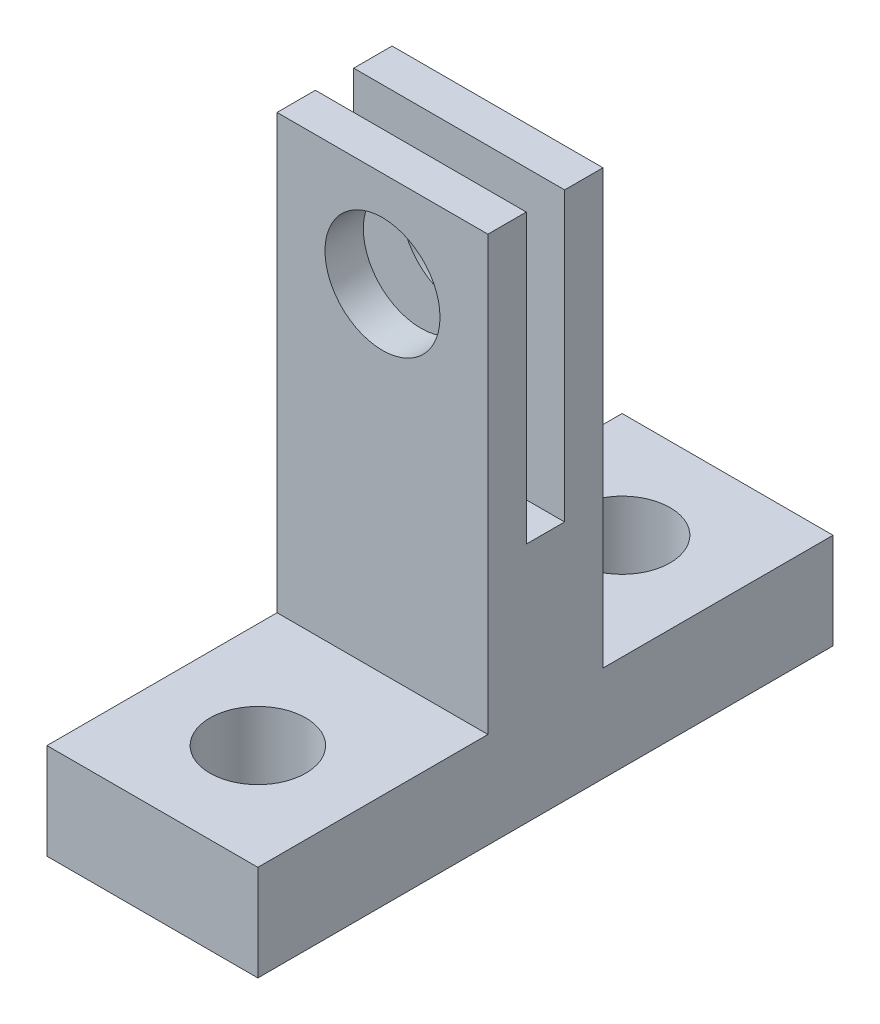
SolidWorks part; units mm, degrees
ref_plane "Front Plane" through (0, 0, 0) normal (0, 0, 1) x (1, 0, 0)
ref_plane "Top Plane" through (0, 0, 0) normal (0, 1, 0) x (1, 0, 0)
ref_plane "Right Plane" through (0, 0, 0) normal (1, 0, 0) x (0, 0, -1)
sketch "Sketch1" plane through (0, 0, 0) normal (1, 0, 0) x (0, 0, -1)
  line L0 (0, 9.8704) -> (0, -6.3) construction
  line L1 (-0.5, 7.5) -> (-0.5, 0)
  line L2 (-0.5, 0) -> (0.5, 0)
  line L3 (-0.5, 7.5) -> (-1.5, 7.5)
  line L4 (-1.5, 7.5) -> (-1.5, -3.8)
  line L6 (-7.5, -6.3) -> (7.5, -6.3)
  line L8 (1.5, 7.5) -> (1.5, -3.8)
  line L9 (0.5, 7.5) -> (1.5, 7.5)
  line L10 (0.5, 7.5) -> (0.5, 0)
  line L11 (-7.5, -6.3) -> (-7.5, -3.8)
  line L12 (1.5, -3.8) -> (7.5, -3.8)
  line L13 (7.5, -3.8) -> (7.5, -6.3)
  line L14 (-7.5, -3.8) -> (-1.5, -3.8)
  point P11 (0, 0)
  dimension "D1" = 6.3
  dimension "D2" = 1
  dimension "D3" = 0.5
  dimension "D4" = 2.5
  dimension "D5" = 15
  dimension "D7" = 7.5
extrude "Boss-Extrude1" add sketch "Sketch1" along normal mid plane 5.5
sketch "Sketch2" plane through (0, -3.8, 0) normal (0, 1, 0) x (1, 0, 0)
  line L0 (0, 0) -> (3.4413, 0) construction
  circle A0 centre (0, -4.75) radius 1.25
  circle A1 centre (0, 4.75) radius 1.25
  dimension "D1" = 2.5
  dimension "D2" = 4.75
extrude "Cut-Extrude1" cut sketch "Sketch2" against normal through all
sketch "Sketch4" plane through (0, 0, 0) normal (0, 0, 1) x (1, 0, 0)
  circle A0 centre (0, 5) radius 1.5
  dimension "D1" = 3
  dimension "D2" = 5
extrude "Cut-Extrude2" cut sketch "Sketch4" against normal through all both and the other way through all
